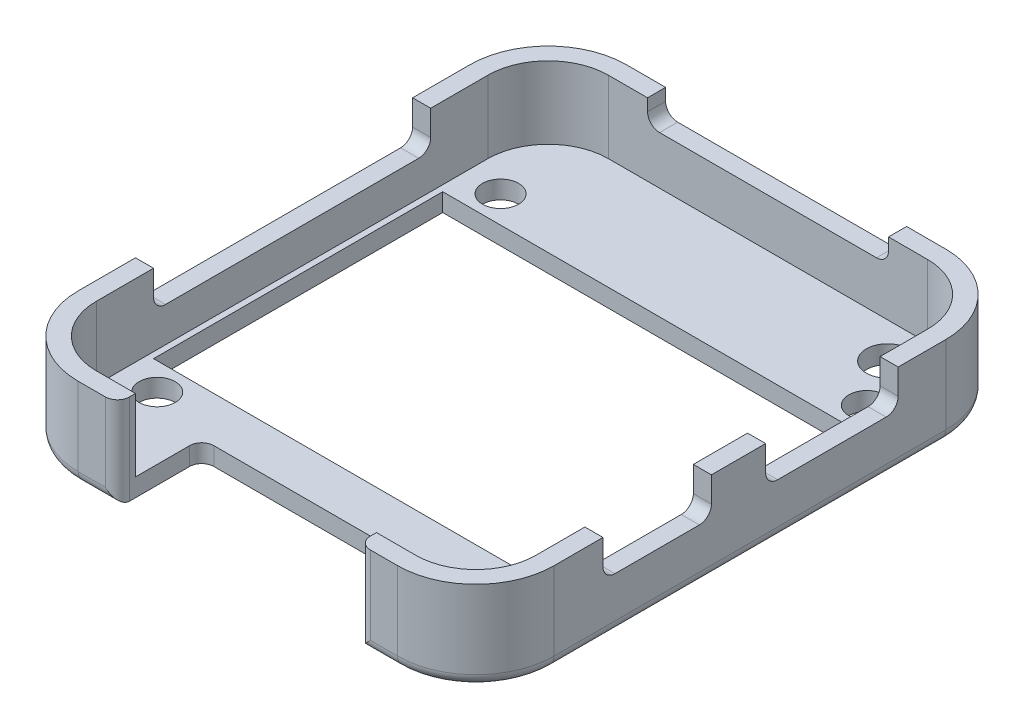
SolidWorks part; units mm, degrees
ref_plane "前视基准面" through (0, 0, 0) normal (0, 0, 1) x (1, 0, 0)
ref_plane "上视基准面" through (0, 0, 0) normal (0, 1, 0) x (1, 0, 0)
ref_plane "右视基准面" through (0, 0, 0) normal (1, 0, 0) x (0, 0, -1)
sketch "草图1" plane through (0, 0, 0) normal (0, 1, 0) x (1, 0, 0)
  line L1 (-13.25, 21.25) -> (13.25, 21.25)
  line L2 (-18.25, 16.25) -> (-18.25, -16.25)
  line L3 (-13.25, -21.25) -> (13.25, -21.25)
  line L4 (18.25, 16.25) -> (18.25, -16.25)
  line L5 (-18.25, 21.25) -> (18.25, -21.25) construction
  line L6 (-18.25, -21.25) -> (18.25, 21.25) construction
  arc A0 (-18.25, -16.25) -> (-13.25, -21.25) centre (-13.25, -16.25) ccw
  arc A1 (13.25, -21.25) -> (18.25, -16.25) centre (13.25, -16.25) ccw
  arc A2 (13.25, 21.25) -> (18.25, 16.25) centre (13.25, 16.25) cw
  arc A3 (-13.25, 21.25) -> (-18.25, 16.25) centre (-13.25, 16.25) ccw
  point P0 (0, 0)
  dimension "D3" = 5
  dimension "D1" = 36.5
  dimension "D2" = 42.5
extrude "凸台-拉伸1" add sketch "草图1" along normal blind 1.5
sketch "草图2" plane through (0, 1.5, 0) normal (0, 1, 0) x (1, 0, 0)
  line L0 (-13.25, -22.75) -> (13.25, -22.75)
  line L1 (19.75, -16.25) -> (19.75, 16.25)
  line L2 (13.25, 22.75) -> (-13.25, 22.75)
  line L3 (-19.75, 16.25) -> (-19.75, -16.25)
  line L4 (-13.25, -21.25) -> (13.25, -21.25)
  line L5 (18.25, -16.25) -> (18.25, 16.25)
  line L6 (13.25, 21.25) -> (-13.25, 21.25)
  line L7 (-18.25, 16.25) -> (-18.25, -16.25)
  line L8 (-13.25, -21.25) -> (13.25, -21.25)
  line L9 (18.25, -16.25) -> (18.25, 16.25)
  line L10 (13.25, 21.25) -> (-13.25, 21.25)
  line L11 (-18.25, 16.25) -> (-18.25, -16.25)
  arc A0 (-19.75, -16.25) -> (-13.25, -22.75) centre (-13.25, -16.25) ccw
  arc A1 (13.25, -22.75) -> (19.75, -16.25) centre (13.25, -16.25) ccw
  arc A2 (19.75, 16.25) -> (13.25, 22.75) centre (13.25, 16.25) ccw
  arc A3 (-13.25, 22.75) -> (-19.75, 16.25) centre (-13.25, 16.25) ccw
  arc A4 (-18.25, -16.25) -> (-13.25, -21.25) centre (-13.25, -16.25) ccw
  arc A5 (13.25, -21.25) -> (18.25, -16.25) centre (13.25, -16.25) ccw
  arc A6 (18.25, 16.25) -> (13.25, 21.25) centre (13.25, 16.25) ccw
  arc A7 (-13.25, 21.25) -> (-18.25, 16.25) centre (-13.25, 16.25) ccw
  arc A8 (-18.25, -16.25) -> (-13.25, -21.25) centre (-13.25, -16.25) ccw
  arc A9 (13.25, -21.25) -> (18.25, -16.25) centre (13.25, -16.25) ccw
  arc A10 (18.25, 16.25) -> (13.25, 21.25) centre (13.25, 16.25) ccw
  arc A11 (-13.25, 21.25) -> (-18.25, 16.25) centre (-13.25, 16.25) ccw
  dimension "D1" = 0
  dimension "D2" = 1.5
extrude "凸台-拉伸2" add sketch "草图2" along normal blind 6 and the other way blind 1.5
sketch "草图3" plane through (0, 0, -22.75) normal (0, 0, -1) x (-1, 0, 0)
  line L0 (-13.25, 7.5) -> (13.25, 7.5) construction
  line L1 (-10, 9.5) -> (10, 9.5)
  line L2 (-10, 9.5) -> (-10, 6.5)
  line L3 (-9, 5.5) -> (9, 5.5)
  line L4 (10, 9.5) -> (10, 6.5)
  line L5 (-10, 9.5) -> (10, 5.5) construction
  line L6 (-10, 5.5) -> (10, 9.5) construction
  arc A0 (9, 5.5) -> (10, 6.5) centre (9, 6.5) ccw
  arc A1 (-10, 6.5) -> (-9, 5.5) centre (-9, 6.5) ccw
  point P0 (0, 7.5)
  dimension "D1" = 1
  dimension "D2" = 2
  dimension "D3" = 20
extrude "切除-拉伸1" cut sketch "草图3" against normal up to next
sketch "草图4" plane through (0, 0, 22.75) normal (0, 0, 1) x (1, 0, 0)
  line L0 (-13.25, 7.5) -> (13.25, 7.5) construction
  line L1 (-10, 17.0877) -> (10, 17.0877)
  line L2 (-10, 17.0877) -> (-10, -2.0877)
  line L3 (-10, -2.0877) -> (10, -2.0877)
  line L4 (10, 17.0877) -> (10, -2.0877)
  line L5 (-10, 17.0877) -> (10, -2.0877) construction
  line L6 (-10, -2.0877) -> (10, 17.0877) construction
  point P0 (0, 7.5)
  dimension "D1" = 20
extrude "切除-拉伸2" cut sketch "草图4" against normal blind 7
fillet "圆角1" radius 1 13 edges at (11.625, 0, 22.75) (-11.625, 0, 22.75) (-17.8462, 0, 20.8462) (-19.75, 0, 0) (-17.8462, 0, -20.8462) (0, 0, -22.75) (17.8462, 0, -20.8462) (19.75, 0, 0) (17.8462, 0, 20.8462) (-10, 3.75, 22.75) (10, 3.75, 22.75) (-10, 0.75, 15.75) (10, 0.75, 15.75)
sketch "草图5" plane through (0, 0, 0) normal (0, -1, 0) x (1, 0, 0)
  line L1 (-17.75, 12) -> (17.75, 12)
  line L2 (-17.75, 12) -> (-17.75, -12)
  line L3 (-17.75, -12) -> (17.75, -12)
  line L4 (17.75, 12) -> (17.75, -12)
  line L5 (-17.75, 12) -> (17.75, -12) construction
  line L6 (-17.75, -12) -> (17.75, 12) construction
  point P0 (0, 0)
  dimension "D1" = 24
  dimension "D2" = 35.5
extrude "切除-拉伸3" cut sketch "草图5" against normal blind 7
sketch "草图6" plane through (0, 0, 0) normal (0, -1, 0) x (1, 0, 0)
  line L0 (0, 0) -> (0, 15.75) construction
  line L1 (-9, 15.75) -> (9, 15.75) construction
  line L2 (0, 0) -> (-17.75, 0) construction
  line L3 (-17.75, 12) -> (-17.75, -12) construction
  circle A0 centre (-15.2, 14.25) radius 1.5
  circle A1 centre (-15.2, -14.25) radius 1.5
  circle A2 centre (15.2, -14.25) radius 1.5
  circle A3 centre (15.2, 14.25) radius 1.5
  dimension "D1" = 3
  dimension "D2" = 30.4
  dimension "D3" = 28.5
extrude "切除-拉伸4" cut sketch "草图6" against normal blind 7
sketch "草图7" plane through (-19.75, 0, 0) normal (-1, 0, 0) x (0, 0, 1)
  line L0 (-16.25, 7.5) -> (16.25, 7.5) construction
  line L1 (-11.5, 10.6) -> (11.5, 10.6)
  line L2 (-11.5, 10.6) -> (-11.5, 5.4)
  line L3 (-10.5, 4.4) -> (10.5, 4.4)
  line L4 (11.5, 10.6) -> (11.5, 5.4)
  line L5 (-11.5, 10.6) -> (11.5, 4.4) construction
  line L6 (-11.5, 4.4) -> (11.5, 10.6) construction
  arc A0 (10.5, 4.4) -> (11.5, 5.4) centre (10.5, 5.4) ccw
  arc A1 (-11.5, 5.4) -> (-10.5, 4.4) centre (-10.5, 5.4) ccw
  point P0 (0, 7.5)
  dimension "D3" = 1
  dimension "D1" = 3.1
  dimension "D2" = 23
extrude "切除-拉伸5" cut sketch "草图7" against normal blind 7
sketch "草图8" plane through (19.75, 0, 0) normal (1, 0, 0) x (0, 0, -1)
  line L0 (-16.25, 7.5) -> (16.25, 7.5) construction
  line L1 (1.3, 10.6) -> (12.3, 10.6)
  line L2 (1.3, 10.6) -> (1.3, 5.4)
  line L3 (2.3, 4.4) -> (11.3, 4.4)
  line L4 (12.3, 10.6) -> (12.3, 5.4)
  line L5 (1.3, 10.6) -> (12.3, 4.4) construction
  line L6 (1.3, 4.4) -> (12.3, 10.6) construction
  line L8 (-12.2, 10.6) -> (-3.2, 10.6)
  line L9 (-12.2, 10.6) -> (-12.2, 5.4)
  line L10 (-11.2, 4.4) -> (-4.2, 4.4)
  line L11 (-3.2, 10.6) -> (-3.2, 5.4)
  line L12 (-12.2, 10.6) -> (-3.2, 4.4) construction
  line L13 (-12.2, 4.4) -> (-3.2, 10.6) construction
  arc A0 (11.3, 4.4) -> (12.3, 5.4) centre (11.3, 5.4) ccw
  arc A1 (1.3, 5.4) -> (2.3, 4.4) centre (2.3, 5.4) ccw
  arc A2 (-4.2, 4.4) -> (-3.2, 5.4) centre (-4.2, 5.4) ccw
  arc A3 (-12.2, 5.4) -> (-11.2, 4.4) centre (-11.2, 5.4) ccw
  point P0 (6.8, 7.5)
  point P7 (-7.7, 7.5)
  dimension "D7" = 1
  dimension "D1" = 11
  dimension "D2" = 3.1
  dimension "D3" = 1.3
  dimension "D4" = 9
  dimension "D5" = 3.1
  dimension "D6" = 3.2
extrude "切除-拉伸6" cut sketch "草图8" against normal blind 7
sketch "草图9" plane through (0, 0, 0) normal (0, -1, 0) x (1, 0, 0)
  circle A0 centre (12.871, -18.289) radius 1.75
  dimension "D1" = 3.5
extrude "切除-拉伸7" cut sketch "草图9" against normal blind 10
